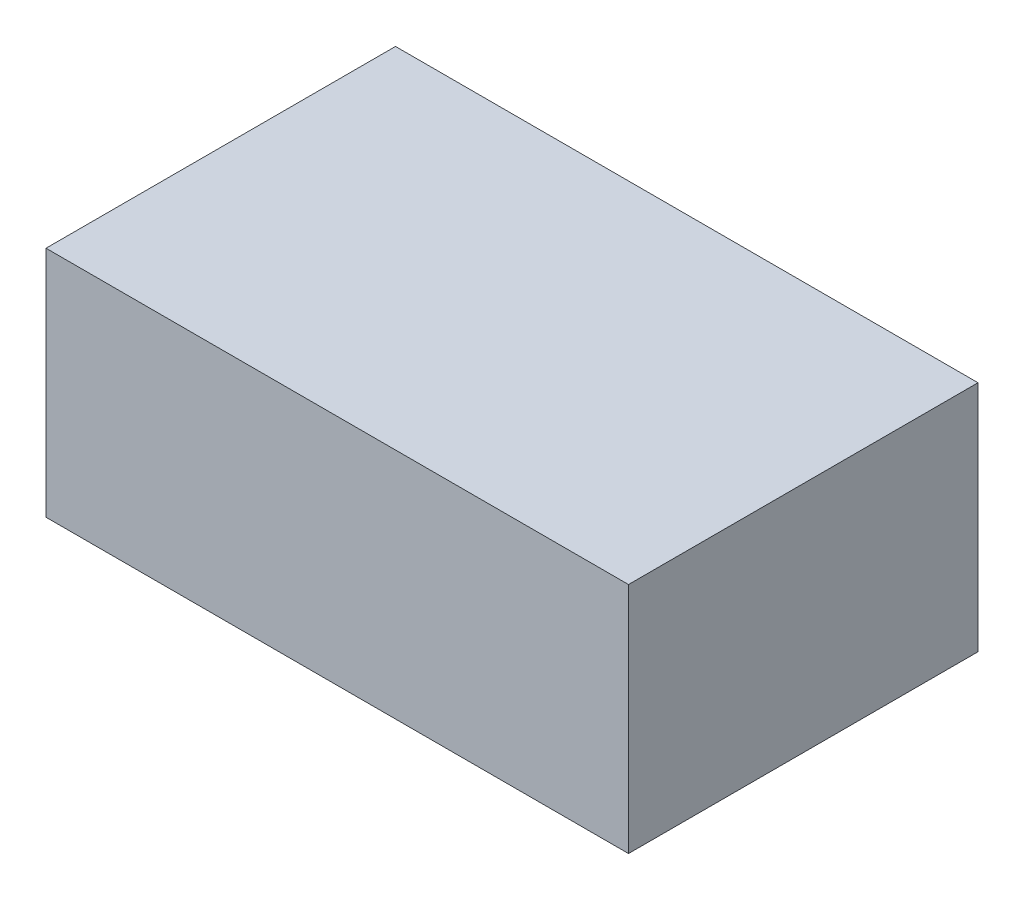
SolidWorks part; units mm, degrees
ref_plane "Front Plane" through (0, 0, 0) normal (0, 0, 1) x (1, 0, 0)
ref_plane "Top Plane" through (0, 0, 0) normal (0, 1, 0) x (1, 0, 0)
ref_plane "Right Plane" through (0, 0, 0) normal (1, 0, 0) x (0, 0, -1)
sketch "Sketch1" plane through (0, 20, 0) normal (0, 1, 0) x (1, 0, 0)
  line L0 (-30.7136, 59.9826) -> (-30.7136, 47.1201) construction
  line L1 (-30.7136, 51.4569) -> (-25.7136, 51.4569)
  line L2 (-30.7136, 51.4569) -> (-30.7136, 48.4569)
  line L3 (-30.7136, 48.4569) -> (-25.7136, 48.4569)
  line L4 (-25.7136, 51.4569) -> (-25.7136, 48.4569)
  line L5 (-25.7136, 47.9826) -> (-25.7136, 59.9826) construction
  dimension "D1" = 3
extrude "Boss-Extrude1" add sketch "Sketch1" along normal blind 2
